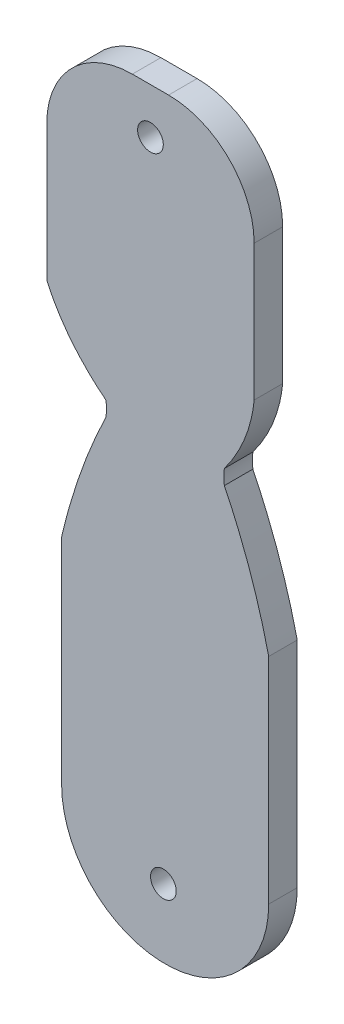
SolidWorks part; units mm, degrees
material "Papel canelado"
ref_plane "Plano frontal" through (0, 0, 0) normal (0, 0, 1) x (1, 0, 0)
ref_plane "Plano superior" through (0, 0, 0) normal (0, 1, 0) x (1, 0, 0)
ref_plane "Plano direito" through (0, 0, 0) normal (1, 0, 0) x (0, 0, -1)
sketch "Esboço1" plane through (0, 0, 0) normal (0, 0, 1) x (1, 0, 0)
  line L0 (0, -1320.3519) -> (0, 64697.245) construction
  line L1 (-18.15, 0) -> (-18.15, 37.6)
  line L2 (15.6, 75.25) -> (15.6, 114.05)
  line L3 (-20.75, 114.05) -> (15.6, 114.05)
  line L4 (18.15, 0) -> (18.15, 37.6)
  line L6 (-20.75, 75.25) -> (-20.75, 114.05)
  arc A0 (-18.15, 0) -> (18.15, 0) centre (0, 0) ccw
  spline S0 degree 2 poles (-18.15, 37.6) (-15.474, 49.1843) (-10.375, 59.65) knots 0 0 0 0.611079 0.611079 0.611079
  spline S1 degree 2 poles (-10.375, 59.65) (-10.1823, 61.008) (-10.375, 62.25) knots 0 0 0 0.26849 0.26849 0.26849
  spline S2 degree 2 poles (10.375, 59.65) (10.1823, 61.008) (10.375, 62.25) knots 0 0 0 0.26849 0.26849 0.26849
  spline S3 degree 2 poles (18.15, 37.6) (15.474, 49.1843) (10.375, 59.65) knots 0 0 0 0.611079 0.611079 0.611079
  spline S4 degree 2 poles (-10.375, 62.25) (-17.3769, 67.7492) (-20.75, 75.25) knots 0 0 0 0.738516 0.738516 0.738516
  spline S5 degree 2 poles (10.375, 62.25) (14.9191, 68.3764) (15.6, 75.25) knots 0 0 0 0.739355 0.739355 0.739355
  point P8 (0, -18.15)
  dimension "D1" = 36.3
  dimension "D2" = 77.8
  dimension "D3" = 55.75
  dimension "D4" = 20.75
  dimension "D5" = 2.6
  dimension "D6" = 13
  dimension "D7" = 20.75
  dimension "D8" = 15.6
  dimension "D9" = 132.2
extrude "Ressalto-extrusão1" add sketch "Esboço1" along normal blind 5
sketch "Esboço2" plane through (0, 0, 5) normal (0, 0, 1) x (1, 0, 0)
  line L0 (-18.15, 37.6) -> (-18.15, 0) construction
  line L1 (-2.575, 114.05) -> (-2.575, 106.05) construction
  line L2 (15.6, 114.05) -> (-20.75, 114.05) construction
  circle A0 centre (-0.31, -6.15) radius 2.25
  arc A1 (-18.15, 0) -> (18.15, 0) centre (0, 0) ccw construction
  circle A2 centre (-2.575, 106.05) radius 2.25
  point P5 (0, -18.15)
  dimension "D3" = 4.5
  dimension "D4" = 8
  dimension "D1" = 12
  dimension "D2" = 17.84
extrude "Corte-extrusão1" cut sketch "Esboço2" against normal through all
fillet "Filete1" radius 15 2 edges at (15.6, 114.05, 2.5) (-20.75, 114.05, 2.5)
